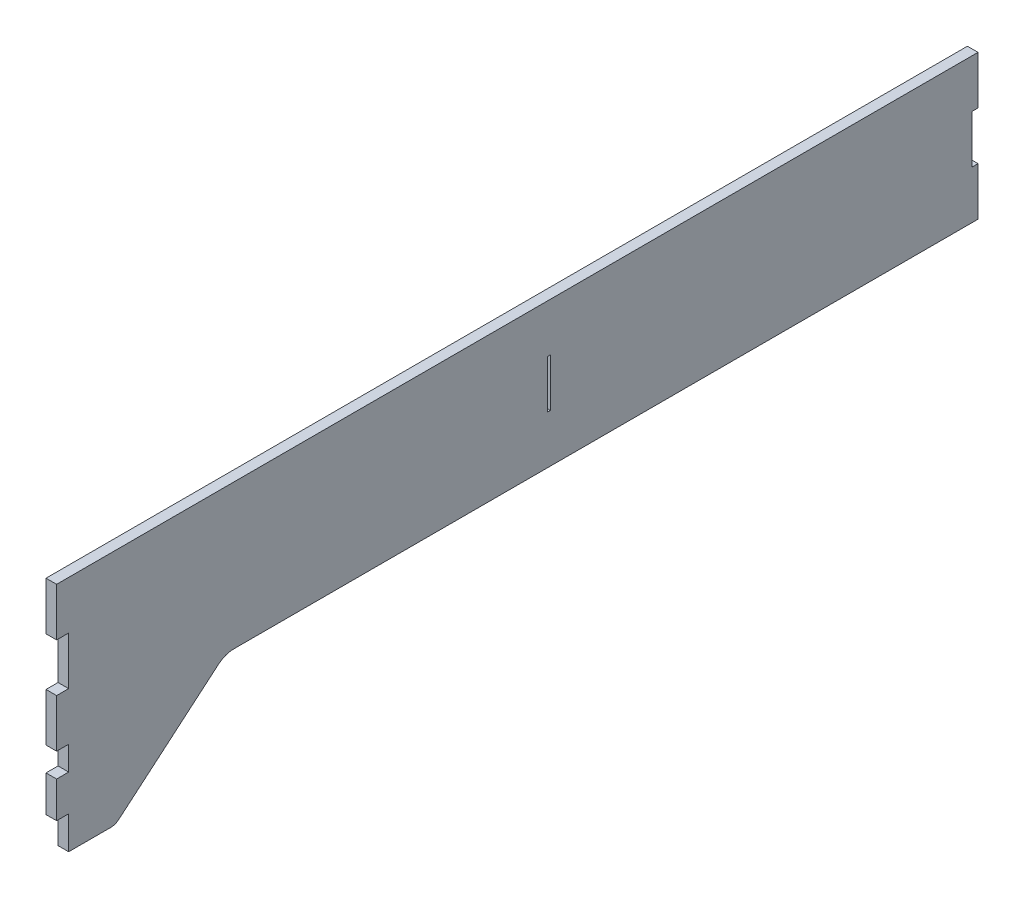
SolidWorks part; units mm, degrees
ref_plane "Front Plane" through (0, 0, 0) normal (0, 0, 1) x (1, 0, 0)
ref_plane "Top Plane" through (0, 0, 0) normal (0, 1, 0) x (1, 0, 0)
ref_plane "Right Plane" through (0, 0, 0) normal (1, 0, 0) x (0, 0, -1)
ref_plane "Plane1" through (-94.488, 0, 0) normal (-1, 0, 0) x (0, -1, 0)
sketch "Sketch1" plane through (-94.488, 0, 0) normal (-1, 0, 0) x (0, -1, 0)
  line L0 (111.125, -457.2) -> (85.725, -457.2)
  line L1 (85.725, -457.2) -> (85.725, -455.6125)
  line L2 (85.725, -455.6125) -> (111.125, -455.6125)
  line L3 (111.125, -455.6125) -> (111.125, -457.2)
  line L4 (111.125, -203.2) -> (85.725, -203.2)
  line L5 (85.725, -203.2) -> (85.725, -196.85)
  line L6 (85.725, -196.85) -> (60.325, -196.85)
  line L7 (60.325, -196.85) -> (60.325, -682.625)
  line L8 (60.325, -682.625) -> (85.725, -682.625)
  line L9 (85.725, -682.625) -> (85.725, -679.45)
  line L10 (85.725, -679.45) -> (111.125, -679.45)
  line L11 (111.125, -679.45) -> (111.125, -682.625)
  line L12 (111.125, -682.625) -> (136.525, -682.625)
  line L13 (136.525, -682.625) -> (136.525, -196.85)
  line L14 (136.525, -196.85) -> (111.125, -196.85)
  line L15 (111.125, -196.85) -> (111.125, -203.2)
  line L16 (136.525, -196.85) -> (185.6232, -196.85) construction
  line L17 (185.6232, -196.85) -> (185.6232, -227.7965) construction
  line L18 (184.1182, -229.5729) -> (139.535, -282.1971)
  line L19 (136.525, -203.2) -> (149.225, -203.2)
  line L20 (149.225, -203.2) -> (149.225, -196.85)
  line L21 (168.275, -196.85) -> (168.275, -203.2)
  line L22 (168.275, -203.2) -> (185.6232, -203.2)
  line L23 (185.6232, -203.2) -> (185.6232, -225.4683)
  line L24 (168.275, -196.85) -> (149.225, -196.85)
  circle A0 centre (130.175, -666.75) radius 1.7526 construction
  circle A1 centre (130.175, -615.95) radius 1.7526 construction
  circle A2 centre (130.175, -565.15) radius 1.7526 construction
  circle A3 centre (130.175, -514.35) radius 1.7526 construction
  circle A4 centre (130.175, -463.55) radius 1.7526 construction
  circle A5 centre (130.175, -412.75) radius 1.7526 construction
  circle A6 centre (130.175, -361.95) radius 1.7526 construction
  circle A7 centre (130.175, -311.15) radius 1.7526 construction
  circle A8 centre (130.175, -260.35) radius 1.7526 construction
  circle A9 centre (130.175, -209.55) radius 1.7526 construction
  arc A10 (184.1182, -229.5729) -> (185.6232, -225.4683) centre (179.2732, -225.4683) ccw
  arc A11 (139.535, -282.1971) -> (136.525, -290.4065) centre (149.225, -290.4065) ccw
  point P38 (136.525, -285.75)
  dimension "D14" = 12.7
  dimension "D15" = 6.35
  dimension "D1" = 222.25
  dimension "D2" = 485.775
  dimension "D3" = 76.2
  dimension "D4" = 3.175
  dimension "D5" = 6.35
  dimension "D6" = 25.4
  dimension "D7" = 25.4
  dimension "D8" = 1.5875
  dimension "D9" = 49.0982
  dimension "D10" = 82.55
  dimension "D11" = 40.271
  dimension "D12" = 19.05
  dimension "D13" = 12.7
extrude "Boss-Extrude1" add sketch "Sketch1" against normal blind 5.588
